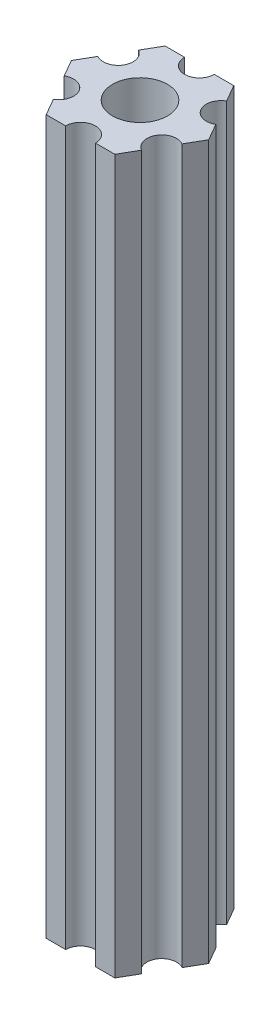
SolidWorks part; units mm, degrees
ref_plane "Front" through (0, 0, 0) normal (0, 0, 1) x (1, 0, 0)
ref_plane "Top" through (0, 0, 0) normal (0, 1, 0) x (1, 0, 0)
ref_plane "Right" through (0, 0, 0) normal (1, 0, 0) x (0, 0, -1)
sketch "Sketch1" plane through (0, 0, 0) normal (0, 1, 0) x (1, 0, 0)
  line L0 (-4.7055, -4.5498) -> (-3.6662, -6.35)
  line L1 (-3.6662, -6.35) -> (-1.5875, -6.35)
  line L2 (1.5875, -6.35) -> (3.6662, -6.35)
  line L3 (3.6662, -6.35) -> (4.7055, -4.5498)
  line L4 (6.293, -1.8002) -> (7.3323, 0)
  line L5 (7.3323, 0) -> (6.293, 1.8002)
  line L6 (4.7055, 4.5498) -> (3.6662, 6.35)
  line L7 (3.6662, 6.35) -> (1.5875, 6.35)
  line L8 (-1.5875, 6.35) -> (-3.6662, 6.35)
  line L9 (-3.6662, 6.35) -> (-4.7055, 4.5498)
  line L10 (-6.293, 1.8002) -> (-7.3323, 0)
  line L11 (-7.3323, 0) -> (-6.293, -1.8002)
  circle A0 centre (0, 0) radius 2.9337
  arc A1 (-6.293, -1.8002) -> (-4.7055, -4.5498) centre (-5.4993, -3.175) cw
  arc A2 (-1.5875, -6.35) -> (1.5875, -6.35) centre (0, -6.35) cw
  arc A3 (4.7055, -4.5498) -> (6.293, -1.8002) centre (5.4993, -3.175) cw
  arc A4 (6.293, 1.8002) -> (4.7055, 4.5498) centre (5.4993, 3.175) cw
  arc A5 (1.5875, 6.35) -> (-1.5875, 6.35) centre (0, 6.35) cw
  arc A6 (-4.7055, 4.5498) -> (-6.293, 1.8002) centre (-5.4993, 3.175) cw
extrude "Boss-Extrude1" add sketch "Sketch1" along normal blind 76.2
